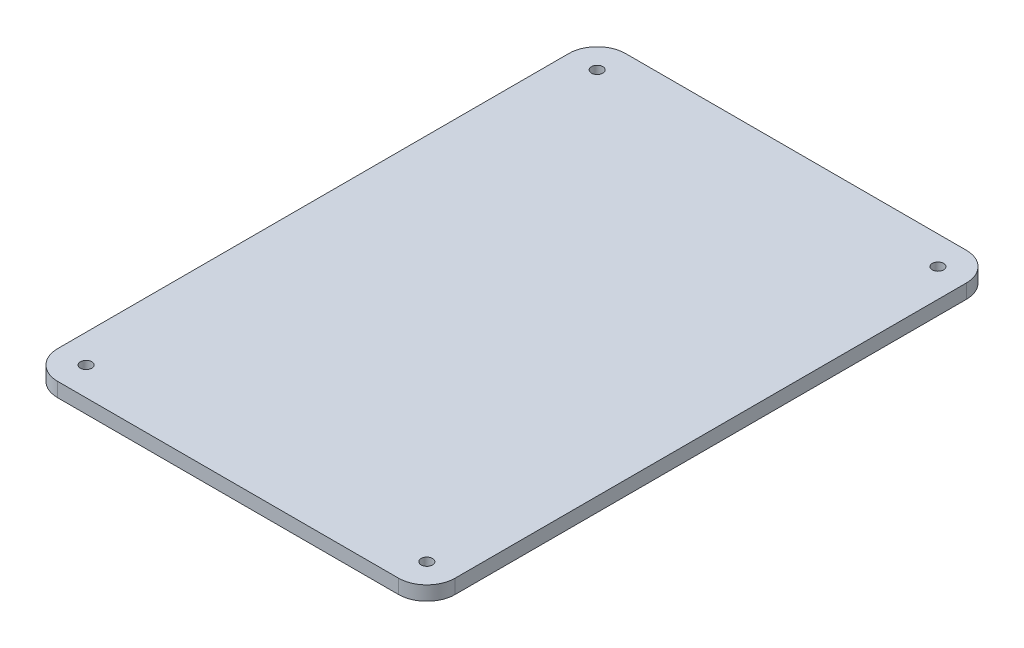
SolidWorks part; units mm, degrees
ref_plane "前视基准面" through (0, 0, 0) normal (0, 0, 1) x (1, 0, 0)
ref_plane "上视基准面" through (0, 0, 0) normal (0, 1, 0) x (1, 0, 0)
ref_plane "右视基准面" through (0, 0, 0) normal (1, 0, 0) x (0, 0, -1)
sketch "草图1" plane through (0, 0, 0) normal (0, 1, 0) x (1, 0, 0)
  line L1 (-90, 90) -> (90, 90)
  line L2 (-90, 90) -> (-90, -90)
  line L3 (-90, -90) -> (90, -90)
  line L4 (90, 90) -> (90, -90)
  line L5 (-90, 90) -> (90, -90) construction
  line L6 (-90, -90) -> (90, 90) construction
  point P0 (0, 0)
  dimension "D1" = 180
  dimension "D2" = 180
extrude "凸台-拉伸1" add sketch "草图1" along normal blind 5
sketch "草图2" plane through (0, 5, 0) normal (0, 1, 0) x (1, 0, 0)
  line L1 (-90, 90) -> (-90, 92.5)
  line L2 (-90, 92.5) -> (90, 92.5)
  line L3 (90, 90) -> (90, 92.5)
  line L4 (-90, 90) -> (90, 90)
extrude "凸台-拉伸2" add sketch "草图2" against normal blind 5
sketch "草图3" plane through (0, 5, 0) normal (0, 1, 0) x (1, 0, 0)
  line L0 (77.5, 92.5) -> (77.5, -90)
  line L1 (90, 92.5) -> (-90, 92.5) construction
  line L2 (-90, -90) -> (90, -90) construction
  line L3 (77.5, -90) -> (90, -90)
  line L4 (90, -90) -> (90, 92.5)
  line L5 (90, 92.5) -> (77.5, 92.5)
  circle A0 centre (70, 80) radius 2.65
  dimension "D1" = 7.5
extrude "切除-拉伸1" cut sketch "草图3" against normal through all both and the other way through all
sketch "草图4" plane through (0, 5, 0) normal (0, 1, 0) x (1, 0, 0)
  line L0 (-90, -90) -> (-90, -92.5)
  line L1 (-90, -92.5) -> (77.5, -92.5)
  line L2 (77.5, -90) -> (77.5, -92.5)
  line L3 (-90, -90) -> (77.5, -90)
  circle A0 centre (-82.5, -85) radius 2.65 construction
  dimension "D1" = 7.5
extrude "凸台-拉伸3" add sketch "草图4" against normal blind 5
fillet "圆角1" radius 10 4 edges at (77.5, 2.5, -92.5) (-90, 2.5, -92.5) (-90, 2.5, 92.5) (77.5, 2.5, 92.5)
sketch "草图5" plane through (0, 5, 0) normal (0, 1, 0) x (1, 0, 0)
  circle A0 centre (70, 80) radius 5.8256
extrude "凸台-拉伸4" add sketch "草图5" against normal blind 5
sketch "草图6" plane through (0, 5, 0) normal (0, 1, 0) x (1, 0, 0)
  circle A0 centre (-82.5, 85) radius 1.5
  circle A1 centre (70, 80) radius 1.5
  circle A2 centre (-82.5, -85) radius 1.5
  circle A3 centre (70, -80) radius 1.5
  dimension "D1" = 3
extrude "切除-拉伸2" cut sketch "草图6" against normal through all both and the other way through all
sketch "草图7" plane through (0, 5, 0) normal (0, 1, 0) x (1, 0, 0)
  line L0 (-70, 100) -> (-70, 95.6176)
  line L1 (70, 100) -> (70, -100)
  line L2 (-70, 100) -> (70, 100)
  line L5 (-70, -100) -> (70, -100)
  line L10 (-70, 92.5) -> (-70, -100)
  line L11 (-70, 95.6176) -> (-70, 92.5)
  line L13 (67.5, 92.5) -> (-80, 92.5) construction
extrude "凸台-拉伸5" add sketch "草图7" against normal blind 5
sketch "草图8" plane through (0, 5, 0) normal (0, 1, 0) x (1, 0, 0)
  line L0 (-70, 100) -> (-70, -100)
  line L1 (-70, -100) -> (-179.8257, -100)
  line L2 (-179.8257, -100) -> (-179.8257, 129.3818)
  line L3 (-179.8257, 129.3818) -> (-70, 100)
  line L4 (70, 100) -> (70, -100)
  line L5 (70, -100) -> (197.4202, -114.5752)
  line L6 (197.4202, -114.5752) -> (173.7553, 114.6909)
  line L7 (173.7553, 114.6909) -> (70, 100)
extrude "切除-拉伸3" cut sketch "草图8" against normal through all both and the other way through all
fillet "圆角2" radius 10 4 edges at (-70, 2.5, 100) (70, 2.5, 100) (70, 2.5, -100) (-70, 2.5, -100)
sketch "草图9" plane through (0, 5, 0) normal (0, 1, 0) x (1, 0, 0)
  circle A0 centre (-60, 90) radius 2
  circle A1 centre (60, 90) radius 2
  circle A2 centre (-60, -90) radius 2
  circle A3 centre (60, -90) radius 2
  point P12 (0, 0)
  point P13 (0, 0)
  point P14 (0, 0)
  point P15 (0, 0)
  dimension "D1" = 4
  dimension "D2" = 4
  dimension "D3" = 4
  dimension "D4" = 4
extrude "切除-拉伸4" cut sketch "草图9" against normal through all both and the other way through all
